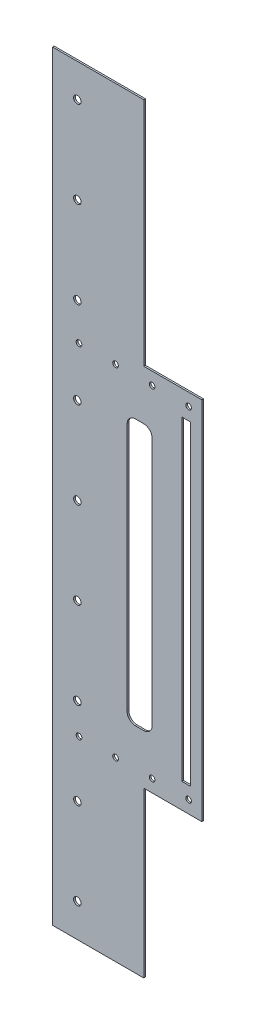
SolidWorks part; units mm, degrees
ref_plane "Спереди" through (0, 0, 0) normal (0, 0, 1) x (1, 0, 0)
ref_plane "Сверху" through (0, 0, 0) normal (0, 1, 0) x (1, 0, 0)
ref_plane "Справа" through (0, 0, 0) normal (1, 0, 0) x (0, 0, -1)
sketch "Эскиз1" plane through (0, 0, 0) normal (0, 0, 1) x (1, 0, 0)
  line L0 (55, 319) -> (55, 458)
  line L1 (0, 0) -> (55, 0)
  line L2 (0, 0) -> (0, 458)
  line L3 (0, 458) -> (55, 458)
  line L4 (55, 0) -> (55, 99)
  line L5 (90, 319) -> (55, 319)
  line L6 (90, 319) -> (90, 99)
  line L7 (90, 99) -> (55, 99)
  dimension "D1" = 55
  dimension "D2" = 458
  dimension "D3" = 220
  dimension "D4" = 99
  dimension "D5" = 90
extrude "Бобышка-Вытянуть1" add sketch "Эскиз1" along normal blind 1
hole_wizard "Отверстие с зазором M41" positions "Эскиз3" profile "Эскиз2" hole size "M4" standard "DIN"
sketch "Эскиз3" plane through (0, 0, 1) normal (0, 0, 1) x (1, 0, 0)
  line L0 (0, 458) -> (0, 0) construction
  line L1 (0, 0) -> (55, 0) construction
  line L2 (15, 20) -> (15, 72.25) construction
  point P0 (15, 20)
  point P12 (15, 72.25)
  point P13 (15, 124.5)
  point P14 (15, 176.75)
  point P15 (15, 229)
  point P16 (15, 281.25)
  point P17 (15, 333.5)
  point P18 (15, 385.75)
  point P19 (15, 438)
  dimension "D1" = 15
  dimension "D2" = 20
  dimension "D3" = 52.25
sketch "Эскиз2" plane through (15, 20, 1) normal (1, 0, 0) x (0, -1, 0)
  line L0 (0, 0) -> (0, 6.3519)
  line L1 (0, 6.3519) -> (2.25, 5)
  line L2 (2.25, 5) -> (2.25, 0)
  line L5 (2.25, 0) -> (0, 0)
  line L10 (0, 6.3519) -> (-2.25, 5) construction
  line L11 (0, -6.35) -> (0, 107.95) construction
  dimension "Диаметр отверстия" = 4.5
  dimension "Глубина отверстия" = 5
  dimension "Угол заточки сверла" = 118
sketch "Эскиз4" plane through (0, 0, 1) normal (0, 0, 1) x (1, 0, 0)
  line L0 (90, 209) -> (83, 209) construction
  line L1 (83, 304) -> (78, 304)
  line L2 (83, 304) -> (83, 114)
  line L3 (83, 114) -> (78, 114)
  line L4 (78, 304) -> (78, 114)
  line L5 (90, 99) -> (90, 319) construction
  line L6 (60, 209) -> (78, 209) construction
  line L7 (60, 289) -> (45, 289)
  line L8 (60, 289) -> (60, 129)
  line L9 (60, 129) -> (45, 129)
  line L10 (45, 289) -> (45, 129)
  dimension "D1" = 190
  dimension "D2" = 5
  dimension "D3" = 7
  dimension "D4" = 160
  dimension "D5" = 15
  dimension "D6" = 45
extrude "Вырез-Вытянуть1" cut sketch "Эскиз4" against normal through all
fillet "Скругление1" radius 5 4 edges at (60, 129, 0.5) (45, 129, 0.5) (45, 289, 0.5) (60, 289, 0.5)
hole_wizard "Отверстие с зазором M31" positions "Эскиз6" profile "Эскиз5" hole size "M3" standard "DIN"
sketch "Эскиз6" plane through (0, 0, 1) normal (0, 0, 1) x (1, 0, 0)
  line L0 (55, 99) -> (90, 99) construction
  line L1 (90, 99) -> (90, 319) construction
  line L2 (90, 319) -> (55, 319) construction
  line L3 (82, 311.5) -> (60, 311.5) construction
  point P0 (82, 106.5)
  point P6 (82, 311.5)
  point P18 (60, 106.5)
  point P19 (60, 311.5)
  point P20 (38, 106.5)
  point P21 (38, 311.5)
  point P22 (16, 106.5)
  point P23 (16, 311.5)
  dimension "D1" = 7.5
  dimension "D2" = 8
  dimension "D3" = 7.5
  dimension "D4" = 22
sketch "Эскиз5" plane through (82, 106.5, 1) normal (1, 0, 0) x (0, -1, 0)
  line L0 (0, 0) -> (0, 6.0215)
  line L1 (0, 6.0215) -> (1.7, 5)
  line L2 (1.7, 5) -> (1.7, 0)
  line L5 (1.7, 0) -> (0, 0)
  line L10 (0, 6.0215) -> (-1.7, 5) construction
  line L11 (0, -6.35) -> (0, 107.95) construction
  dimension "Диаметр отверстия" = 3.4
  dimension "Глубина отверстия" = 5
  dimension "Угол заточки сверла" = 118
